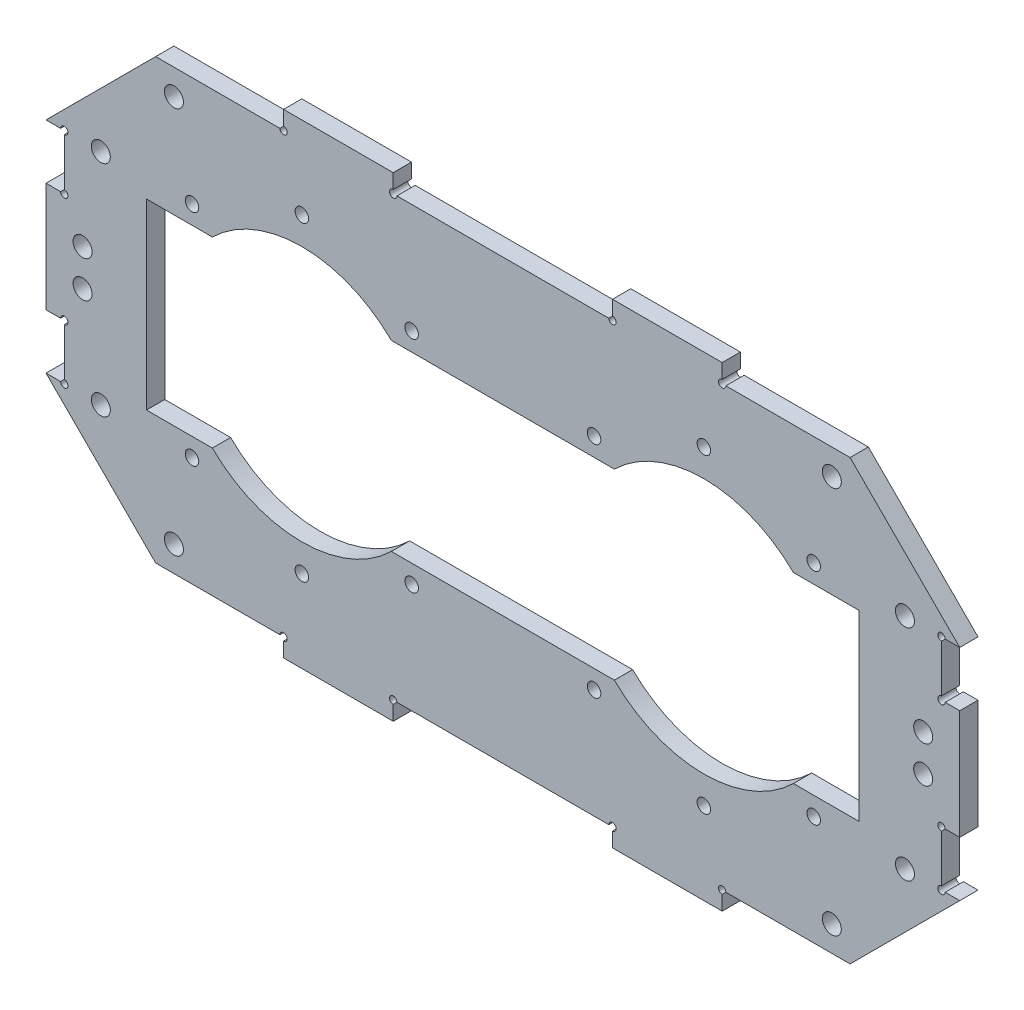
SolidWorks part; units mm, degrees
ref_plane "前视基准面" through (0, 0, 0) normal (0, 0, 1) x (1, 0, 0)
ref_plane "上视基准面" through (0, 0, 0) normal (0, 1, 0) x (1, 0, 0)
ref_plane "右视基准面" through (0, 0, 0) normal (1, 0, 0) x (0, 0, -1)
other "Configuration Table"
sketch "草图1" plane through (0, 0, 0) normal (0, 0, 1) x (1, 0, 0)
  line L36 (95.3994, 59.7004) -> (125.3994, 29.7004)
  line L37 (125.3994, -30.2996) -> (125.3994, 29.7004)
  line L38 (95.3994, -60.2996) -> (125.3994, -30.2996)
  line L39 (-94.6006, -60.2996) -> (95.3994, -60.2996)
  line L40 (95.3994, 59.7004) -> (-94.6006, 59.7004)
  line L41 (-94.6006, -60.2996) -> (-124.6006, -30.2996)
  line L42 (-124.6006, 29.7004) -> (-124.6006, -30.2996)
  line L43 (-94.6006, 59.7004) -> (-124.6006, 29.7004)
extrude "凸台-拉伸1" add sketch "草图1" along normal blind 5
sketch "草图2" plane through (0, 0, 5) normal (0, 0, 1) x (1, 0, 0)
  line L0 (0.3994, 59.7004) -> (0.3994, -60.2996) construction
  line L1 (-124.6006, 29.7004) -> (-119.6006, 29.7004)
  line L2 (-124.6006, 29.7004) -> (-124.6006, 14.7004)
  line L3 (-124.6006, 14.7004) -> (-119.6006, 14.7004)
  line L4 (-119.6006, 29.7004) -> (-119.6006, 14.7004)
  line L5 (-124.6006, -30.2996) -> (-119.6006, -30.2996)
  line L6 (-124.6006, -30.2996) -> (-124.6006, -15.2996)
  line L7 (-124.6006, -15.2996) -> (-119.6006, -15.2996)
  line L8 (95.3994, 59.7004) -> (-94.6006, 59.7004)
  line L9 (-94.6006, 59.7004) -> (-124.6006, 29.7004)
  line L10 (-124.6006, 29.7004) -> (-124.6006, -30.2996)
  line L11 (-124.6006, -30.2996) -> (-94.6006, -60.2996)
  line L12 (-94.6006, -60.2996) -> (95.3994, -60.2996)
  line L13 (95.3994, -60.2996) -> (125.3994, -30.2996)
  line L14 (125.3994, -30.2996) -> (125.3994, 29.7004)
  line L15 (125.3994, 29.7004) -> (95.3994, 59.7004)
  line L16 (95.3994, 59.7004) -> (-94.6006, 59.7004)
  line L17 (-94.6006, 59.7004) -> (-124.6006, 29.7004)
  line L18 (-124.6006, 29.7004) -> (-124.6006, -30.2996)
  line L19 (-124.6006, -30.2996) -> (-94.6006, -60.2996)
  line L20 (-94.6006, -60.2996) -> (95.3994, -60.2996)
  line L21 (95.3994, -60.2996) -> (125.3994, -30.2996)
  line L22 (125.3994, -30.2996) -> (125.3994, 29.7004)
  line L23 (125.3994, 29.7004) -> (95.3994, 59.7004)
  line L24 (-119.6006, -30.2996) -> (-119.6006, -15.2996)
  line L25 (125.3994, -30.2996) -> (120.3994, -30.2996)
  line L26 (120.3994, -30.2996) -> (120.3994, -15.2996)
  line L27 (125.3994, -15.2996) -> (120.3994, -15.2996)
  line L28 (125.3994, -30.2996) -> (125.3994, -15.2996)
  line L29 (125.3994, 29.7004) -> (125.3994, 14.7004)
  line L30 (125.3994, 14.7004) -> (120.3994, 14.7004)
  line L31 (125.3994, 29.7004) -> (120.3994, 29.7004)
  line L32 (120.3994, 29.7004) -> (120.3994, 14.7004)
  line M20 (-124.6006, 29.7004) -> (-124.6006, -30.2996)
  line M24 (125.3994, -30.2996) -> (125.3994, 29.7004)
  dimension "D2" = 5
  dimension "D3" = 5
  dimension "D4" = 15
  dimension "D5" = 15
  dimension "D1" = 0
extrude "切除-拉伸1" cut sketch "草图2" against normal blind 5 contours L4 L1 L3 M20 | L5 L24 L7 M20 | L27 L26 L25 M24 | L31 L32 L30 M24
sketch "草图3" plane through (0, 0, 5) normal (0, 0, 1) x (1, 0, 0)
  line L0 (-124.6006, 14.7004) -> (-124.6006, -15.2996) construction
  line L1 (-94.6006, -60.2996) -> (95.3994, -60.2996) construction
  line L2 (0.3994, 59.7004) -> (0.3994, -60.2996) construction
  line L3 (95.3994, 59.7004) -> (-94.6006, 59.7004) construction
  line L5 (82.8994, 24.7004) -> (112.8994, 24.7004)
  line L7 (82.8994, -25.2996) -> (112.8994, -25.2996)
  line L8 (112.8994, 24.7004) -> (112.8994, -25.2996)
  line L9 (82.8994, 24.7004) -> (112.8994, -25.2996) construction
  line L10 (82.8994, -25.2996) -> (112.8994, 24.7004) construction
  line L11 (-112.1006, -25.2996) -> (112.8994, -25.2996)
  line L12 (-112.1006, -25.2996) -> (-112.1006, 24.7004)
  line L13 (-112.1006, 24.7004) -> (112.8994, 24.7004)
  line L14 (112.8994, -25.2996) -> (112.8994, 24.7004)
  line L15 (-112.1006, -25.2996) -> (112.8994, 24.7004) construction
  line L16 (-112.1006, 24.7004) -> (112.8994, -25.2996) construction
  line L24 (120.3994, 29.7004) -> (125.3994, 29.7004)
  line L25 (125.3994, 29.7004) -> (95.3994, 59.7004)
  line L26 (95.3994, 59.7004) -> (-94.6006, 59.7004)
  line L27 (-94.6006, 59.7004) -> (-124.6006, 29.7004)
  line L28 (-124.6006, 29.7004) -> (-119.6006, 29.7004)
  line L29 (-119.6006, 29.7004) -> (-119.6006, 14.7004)
  line L30 (-119.6006, 14.7004) -> (-124.6006, 14.7004)
  line L31 (-124.6006, 14.7004) -> (-124.6006, -15.2996)
  line L32 (-124.6006, -15.2996) -> (-119.6006, -15.2996)
  line L33 (-119.6006, -15.2996) -> (-119.6006, -30.2996)
  line L34 (-119.6006, -30.2996) -> (-124.6006, -30.2996)
  line L35 (-124.6006, -30.2996) -> (-94.6006, -60.2996)
  line L36 (-94.6006, -60.2996) -> (95.3994, -60.2996)
  line L37 (95.3994, -60.2996) -> (125.3994, -30.2996)
  line L38 (125.3994, -30.2996) -> (120.3994, -30.2996)
  line L39 (120.3994, -30.2996) -> (120.3994, -15.2996)
  line L40 (120.3994, -15.2996) -> (125.3994, -15.2996)
  line L41 (125.3994, -15.2996) -> (125.3994, 14.7004)
  line L42 (125.3994, 14.7004) -> (120.3994, 14.7004)
  line L43 (120.3994, 14.7004) -> (120.3994, 29.7004)
  line L44 (120.3994, 29.7004) -> (125.3994, 29.7004)
  line L45 (125.3994, 29.7004) -> (95.3994, 59.7004)
  line L46 (95.3994, 59.7004) -> (-94.6006, 59.7004)
  line L47 (-94.6006, 59.7004) -> (-124.6006, 29.7004)
  line L48 (-124.6006, 29.7004) -> (-119.6006, 29.7004)
  line L49 (-119.6006, 29.7004) -> (-119.6006, 14.7004)
  line L50 (-119.6006, 14.7004) -> (-124.6006, 14.7004)
  line L51 (-124.6006, 14.7004) -> (-124.6006, -15.2996)
  line L52 (-124.6006, -15.2996) -> (-119.6006, -15.2996)
  line L53 (-119.6006, -15.2996) -> (-119.6006, -30.2996)
  line L54 (-119.6006, -30.2996) -> (-124.6006, -30.2996)
  line L55 (-124.6006, -30.2996) -> (-94.6006, -60.2996)
  line L56 (-94.6006, -60.2996) -> (95.3994, -60.2996)
  line L57 (95.3994, -60.2996) -> (125.3994, -30.2996)
  line L58 (125.3994, -30.2996) -> (120.3994, -30.2996)
  line L59 (120.3994, -30.2996) -> (120.3994, -15.2996)
  line L60 (120.3994, -15.2996) -> (125.3994, -15.2996)
  line L61 (125.3994, -15.2996) -> (125.3994, 14.7004)
  line L62 (125.3994, 14.7004) -> (120.3994, 14.7004)
  line L63 (120.3994, 14.7004) -> (120.3994, 29.7004)
  circle A0 centre (-54.6006, -0.2996) radius 42.5 construction
  circle A1 centre (55.3994, -0.2996) radius 42.5 construction
  circle A2 centre (-54.6006, 42.2004) radius 1.85
  circle A3 centre (-24.5485, 29.7525) radius 1.85
  circle A4 centre (-12.1006, -0.2996) radius 1.85
  circle A5 centre (-24.5485, -30.3516) radius 1.85
  circle A6 centre (-54.6006, -42.7996) radius 1.85
  circle A7 centre (-84.6526, -30.3516) radius 1.85
  circle A8 centre (-97.1006, -0.2996) radius 1.85
  circle A9 centre (-84.6526, 29.7525) radius 1.85
  circle A10 centre (55.3994, 42.2004) radius 1.85
  circle A11 centre (85.4515, 29.7525) radius 1.85
  circle A12 centre (97.8994, -0.2996) radius 1.85
  circle A13 centre (85.4515, -30.3516) radius 1.85
  circle A14 centre (55.3994, -42.7996) radius 1.85
  circle A15 centre (25.3474, -30.3516) radius 1.85
  circle A16 centre (12.8994, -0.2996) radius 1.85
  circle A17 centre (25.3474, 29.7525) radius 1.85
  circle A18 centre (55.3994, -0.2996) radius 35 construction
  circle A19 centre (-54.6006, -0.2996) radius 35 construction
  point P50 (-54.6006, -0.2996)
  point P68 (55.3994, -0.2996)
  point P72 (0.3994, -0.2996)
  dimension "D1" = 85
  dimension "D3" = 60
  dimension "D5" = 3.7
  dimension "D7" = 3.7
  dimension "D9" = 70
  dimension "D10" = 70
  dimension "D2" = 70
  dimension "D11" = 50
  dimension "D12" = 30
  dimension "D13" = 225
  dimension "D14" = 112.5
  dimension "D4" = 0
  dimension "D6" = 8
  dimension "D8" = 8
extrude "切除-拉伸3" cut sketch "草图3" against normal blind 5 contours L13 L12 L11 L7 L8 L5 A16 A12 A8 A4 | A7 | A6 | A5 | A4 | A3 | A15 | A14 | A13 | A11 | A10 | A17 | A16 | A12 | A2 | A9
sketch "草图4" plane through (0, 0, 5) normal (0, 0, 1) x (1, 0, 0)
  line L0 (125.3994, -30.2996) -> (125.3994, 29.7004) construction
  line L1 (-94.6006, 59.7004) -> (-124.6006, 29.7004) construction
  line L2 (95.3994, 59.7004) -> (-94.6006, 59.7004) construction
  line L3 (125.3994, 29.7004) -> (95.3994, 59.7004) construction
  line L4 (-124.6006, -30.2996) -> (-94.6006, -60.2996) construction
  line L5 (-94.6006, -60.2996) -> (95.3994, -60.2996) construction
  line L6 (95.3994, -60.2996) -> (125.3994, -30.2996) construction
  line L7 (-124.6006, 29.7004) -> (-124.6006, -30.2996) construction
  line L8 (125.3994, 29.7004) -> (125.3994, 14.7004) construction
  line L9 (125.3994, 14.7004) -> (120.3994, 14.7004) construction
  line L10 (120.3994, 29.7004) -> (120.3994, 14.7004) construction
  line L11 (125.3994, 29.7004) -> (120.3994, 29.7004) construction
  line L12 (125.3994, -30.2996) -> (120.3994, -30.2996) construction
  line L13 (120.3994, -30.2996) -> (120.3994, -15.2996) construction
  line L14 (125.3994, -15.2996) -> (120.3994, -15.2996) construction
  line L15 (125.3994, -30.2996) -> (125.3994, -15.2996) construction
  line L16 (-124.6006, -30.2996) -> (-119.6006, -30.2996) construction
  line L17 (-119.6006, -30.2996) -> (-119.6006, -15.2996) construction
  line L18 (-124.6006, -15.2996) -> (-119.6006, -15.2996) construction
  line L19 (-124.6006, -30.2996) -> (-124.6006, -15.2996) construction
  line L20 (120.3994, 29.7004) -> (125.3994, 29.7004)
  line L21 (125.3994, 29.7004) -> (95.3994, 59.7004)
  line L22 (95.3994, 59.7004) -> (-94.6006, 59.7004)
  line L23 (-94.6006, 59.7004) -> (-124.6006, 29.7004)
  line L24 (-124.6006, 29.7004) -> (-119.6006, 29.7004)
  line L25 (-119.6006, 29.7004) -> (-119.6006, 14.7004)
  line L26 (-119.6006, 14.7004) -> (-124.6006, 14.7004)
  line L27 (-124.6006, 14.7004) -> (-124.6006, -15.2996)
  line L28 (-124.6006, -15.2996) -> (-119.6006, -15.2996)
  line L29 (-119.6006, -15.2996) -> (-119.6006, -30.2996)
  line L30 (-119.6006, -30.2996) -> (-124.6006, -30.2996)
  line L31 (-124.6006, -30.2996) -> (-94.6006, -60.2996)
  line L32 (-94.6006, -60.2996) -> (95.3994, -60.2996)
  line L33 (95.3994, -60.2996) -> (125.3994, -30.2996)
  line L34 (125.3994, -30.2996) -> (120.3994, -30.2996)
  line L35 (120.3994, -30.2996) -> (120.3994, -15.2996)
  line L36 (120.3994, -15.2996) -> (125.3994, -15.2996)
  line L37 (125.3994, -15.2996) -> (125.3994, 14.7004)
  line L38 (125.3994, 14.7004) -> (120.3994, 14.7004)
  line L39 (120.3994, 14.7004) -> (120.3994, 29.7004)
  line L40 (120.3994, 29.7004) -> (125.3994, 29.7004)
  line L41 (125.3994, 29.7004) -> (95.3994, 59.7004)
  line L42 (95.3994, 59.7004) -> (-94.6006, 59.7004)
  line L43 (-94.6006, 59.7004) -> (-124.6006, 29.7004)
  line L44 (-124.6006, 29.7004) -> (-119.6006, 29.7004)
  line L45 (-119.6006, 29.7004) -> (-119.6006, 14.7004)
  line L46 (-119.6006, 14.7004) -> (-124.6006, 14.7004)
  line L47 (-124.6006, 14.7004) -> (-124.6006, -15.2996)
  line L48 (-124.6006, -15.2996) -> (-119.6006, -15.2996)
  line L49 (-119.6006, -15.2996) -> (-119.6006, -30.2996)
  line L50 (-119.6006, -30.2996) -> (-124.6006, -30.2996)
  line L51 (-124.6006, -30.2996) -> (-94.6006, -60.2996)
  line L52 (-94.6006, -60.2996) -> (95.3994, -60.2996)
  line L53 (95.3994, -60.2996) -> (125.3994, -30.2996)
  line L54 (125.3994, -30.2996) -> (120.3994, -30.2996)
  line L55 (120.3994, -30.2996) -> (120.3994, -15.2996)
  line L56 (120.3994, -15.2996) -> (125.3994, -15.2996)
  line L57 (125.3994, -15.2996) -> (125.3994, 14.7004)
  line L58 (125.3994, 14.7004) -> (120.3994, 14.7004)
  line L59 (120.3994, 14.7004) -> (120.3994, 29.7004)
  line L60 (-124.6006, 29.7004) -> (-119.6006, 29.7004) construction
  line L61 (-119.6006, 29.7004) -> (-119.6006, 14.7004) construction
  line L62 (-124.6006, 14.7004) -> (-119.6006, 14.7004) construction
  line L63 (-124.6006, 29.7004) -> (-124.6006, 14.7004) construction
  line L64 (125.3994, -30.2996) -> (125.3994, 29.7004)
  line L65 (-94.6006, 59.7004) -> (-124.6006, 29.7004)
  line L66 (95.3994, 59.7004) -> (-94.6006, 59.7004)
  line L67 (125.3994, 29.7004) -> (95.3994, 59.7004)
  line L68 (-124.6006, -30.2996) -> (-94.6006, -60.2996)
  line L69 (-94.6006, -60.2996) -> (95.3994, -60.2996)
  line L70 (95.3994, -60.2996) -> (125.3994, -30.2996)
  line L71 (-124.6006, 29.7004) -> (-124.6006, -30.2996)
  line L72 (125.3994, 29.7004) -> (125.3994, 14.7004)
  line L73 (125.3994, 14.7004) -> (120.3994, 14.7004)
  line L74 (120.3994, 29.7004) -> (120.3994, 14.7004)
  line L75 (125.3994, 29.7004) -> (120.3994, 29.7004)
  line L76 (125.3994, -30.2996) -> (120.3994, -30.2996)
  line L77 (120.3994, -30.2996) -> (120.3994, -15.2996)
  line L78 (125.3994, -15.2996) -> (120.3994, -15.2996)
  line L79 (125.3994, -30.2996) -> (125.3994, -15.2996)
  line L80 (-124.6006, -30.2996) -> (-119.6006, -30.2996)
  line L81 (-119.6006, -30.2996) -> (-119.6006, -15.2996)
  line L82 (-124.6006, -15.2996) -> (-119.6006, -15.2996)
  line L83 (-124.6006, -30.2996) -> (-124.6006, -15.2996)
  line L84 (-124.6006, 29.7004) -> (-119.6006, 29.7004)
  line L85 (-119.6006, 29.7004) -> (-119.6006, 14.7004)
  line L86 (-124.6006, 14.7004) -> (-119.6006, 14.7004)
  line L87 (-124.6006, 29.7004) -> (-124.6006, 14.7004)
  line L88 (82.8994, -25.2996) -> (112.8994, -25.2996) construction
  line L89 (112.8994, 24.7004) -> (112.8994, -25.2996) construction
  line L90 (-112.1006, -25.2996) -> (112.8994, -25.2996) construction
  line L91 (-112.1006, -25.2996) -> (-112.1006, 24.7004) construction
  line L92 (-112.1006, 24.7004) -> (112.8994, 24.7004) construction
  line L93 (112.8994, -25.2996) -> (112.8994, 24.7004) construction
  line L94 (82.8994, 24.7004) -> (112.8994, 24.7004) construction
  line L95 (82.8994, -25.2996) -> (112.8994, -25.2996)
  line L96 (112.8994, 24.7004) -> (112.8994, -25.2996)
  line L97 (-112.1006, -25.2996) -> (112.8994, -25.2996)
  line L98 (-112.1006, -25.2996) -> (-112.1006, 24.7004)
  line L99 (-112.1006, 24.7004) -> (112.8994, 24.7004)
  line L100 (112.8994, -25.2996) -> (112.8994, 24.7004)
  line L101 (82.8994, 24.7004) -> (112.8994, 24.7004)
  line L102 (0.3994, 59.7004) -> (0.3994, -60.2996) construction
  line L108 (120.3994, 14.7004) -> (120.3994, 29.7004)
  line L109 (120.3994, 29.7004) -> (125.3994, 29.7004)
  line L110 (125.3994, 29.7004) -> (95.3994, 59.7004)
  line L111 (95.3994, 59.7004) -> (-94.6006, 59.7004)
  line L112 (-94.6006, 59.7004) -> (-124.6006, 29.7004)
  line L113 (-124.6006, 29.7004) -> (-119.6006, 29.7004)
  line L114 (-119.6006, 29.7004) -> (-119.6006, 14.7004)
  line L115 (-119.6006, 14.7004) -> (-124.6006, 14.7004)
  line L116 (-124.6006, 14.7004) -> (-124.6006, -15.2996)
  line L117 (-124.6006, -15.2996) -> (-119.6006, -15.2996)
  line L118 (-119.6006, -15.2996) -> (-119.6006, -30.2996)
  line L119 (-119.6006, -30.2996) -> (-124.6006, -30.2996)
  line L120 (-124.6006, -30.2996) -> (-94.6006, -60.2996)
  line L121 (-94.6006, -60.2996) -> (95.3994, -60.2996)
  line L122 (95.3994, -60.2996) -> (125.3994, -30.2996)
  line L123 (125.3994, -30.2996) -> (120.3994, -30.2996)
  line L124 (120.3994, -30.2996) -> (120.3994, -15.2996)
  line L125 (120.3994, -15.2996) -> (125.3994, -15.2996)
  line L126 (125.3994, -15.2996) -> (125.3994, 14.7004)
  line L127 (125.3994, 14.7004) -> (120.3994, 14.7004)
  line L128 (120.3994, 14.7004) -> (120.3994, 29.7004)
  line L129 (120.3994, 29.7004) -> (125.3994, 29.7004)
  line L130 (125.3994, 29.7004) -> (95.3994, 59.7004)
  line L131 (95.3994, 59.7004) -> (-94.6006, 59.7004)
  line L132 (-94.6006, 59.7004) -> (-124.6006, 29.7004)
  line L133 (-124.6006, 29.7004) -> (-119.6006, 29.7004)
  line L134 (-119.6006, 29.7004) -> (-119.6006, 14.7004)
  line L135 (-119.6006, 14.7004) -> (-124.6006, 14.7004)
  line L136 (-124.6006, 14.7004) -> (-124.6006, -15.2996)
  line L137 (-124.6006, -15.2996) -> (-119.6006, -15.2996)
  line L138 (-119.6006, -15.2996) -> (-119.6006, -30.2996)
  line L139 (-119.6006, -30.2996) -> (-124.6006, -30.2996)
  line L140 (-124.6006, -30.2996) -> (-94.6006, -60.2996)
  line L141 (-94.6006, -60.2996) -> (95.3994, -60.2996)
  line L142 (95.3994, -60.2996) -> (125.3994, -30.2996)
  line L143 (125.3994, -30.2996) -> (120.3994, -30.2996)
  line L144 (120.3994, -30.2996) -> (120.3994, -15.2996)
  line L145 (120.3994, -15.2996) -> (125.3994, -15.2996)
  line L146 (125.3994, -15.2996) -> (125.3994, 14.7004)
  line L147 (125.3994, 14.7004) -> (120.3994, 14.7004)
  circle A0 centre (-54.6006, -0.2996) radius 35
  circle A1 centre (-12.1006, -0.2996) radius 1.85
  circle A2 centre (-12.1006, -0.2996) radius 1.85
  circle A3 centre (-24.5485, 29.7525) radius 1.85
  circle A4 centre (-24.5485, 29.7525) radius 1.85
  circle A5 centre (-54.6006, 42.2004) radius 1.85
  circle A6 centre (-54.6006, 42.2004) radius 1.85
  circle A7 centre (-97.1006, -0.2996) radius 1.85
  circle A8 centre (-97.1006, -0.2996) radius 1.85
  circle A9 centre (-84.6526, -30.3516) radius 1.85
  circle A10 centre (-84.6526, -30.3516) radius 1.85
  circle A11 centre (-54.6006, -42.7996) radius 1.85
  circle A12 centre (-54.6006, -42.7996) radius 1.85
  circle A13 centre (-24.5485, -30.3516) radius 1.85
  circle A14 centre (-24.5485, -30.3516) radius 1.85
  circle A15 centre (25.3474, -30.3516) radius 1.85
  circle A16 centre (25.3474, -30.3516) radius 1.85
  circle A17 centre (55.3994, -42.7996) radius 1.85
  circle A18 centre (55.3994, -42.7996) radius 1.85
  circle A19 centre (85.4515, -30.3516) radius 1.85
  circle A20 centre (85.4515, -30.3516) radius 1.85
  circle A21 centre (97.8994, -0.2996) radius 1.85
  circle A22 centre (97.8994, -0.2996) radius 1.85
  circle A23 centre (85.4515, 29.7525) radius 1.85
  circle A24 centre (85.4515, 29.7525) radius 1.85
  circle A25 centre (55.3994, 42.2004) radius 1.85
  circle A26 centre (55.3994, 42.2004) radius 1.85
  circle A27 centre (-84.6526, 29.7525) radius 1.85
  circle A28 centre (-84.6526, 29.7525) radius 1.85
  circle A29 centre (25.3474, 29.7525) radius 1.85
  circle A30 centre (25.3474, 29.7525) radius 1.85
  circle A31 centre (12.8994, -0.2996) radius 1.85
  circle A32 centre (12.8994, -0.2996) radius 1.85
  circle A33 centre (55.3994, -0.2996) radius 35
  dimension "D20" = 60
  dimension "D21" = 70
  dimension "D19" = 70
  dimension "D1" = 0
  dimension "D2" = 0
  dimension "D3" = 0
  dimension "D4" = 0
  dimension "D5" = 0
  dimension "D6" = 0
  dimension "D7" = 0
  dimension "D8" = 0
  dimension "D9" = 0
  dimension "D10" = 0
  dimension "D11" = 0
  dimension "D12" = 0
  dimension "D13" = 0
  dimension "D14" = 0
  dimension "D15" = 0
  dimension "D16" = 0
  dimension "D17" = 0
  dimension "D18" = 0
extrude "切除-拉伸4" cut sketch "草图4" against normal blind 5 contours L99 A0 | L97 A0 | A33 L97 | A33 L99
sketch "草图5" plane through (0, 0, 5) normal (0, 0, 1) x (1, 0, 0)
  line L0 (0.3994, 59.7004) -> (0.3994, -60.2996)
  line L20 (120.3994, 29.7004) -> (125.3994, 29.7004)
  line L21 (125.3994, 29.7004) -> (95.3994, 59.7004)
  line L22 (95.3994, 59.7004) -> (-94.6006, 59.7004)
  line L23 (-94.6006, 59.7004) -> (-124.6006, 29.7004)
  line L24 (-124.6006, 29.7004) -> (-119.6006, 29.7004)
  line L25 (-119.6006, 29.7004) -> (-119.6006, 14.7004)
  line L26 (-119.6006, 14.7004) -> (-124.6006, 14.7004)
  line L27 (-124.6006, 14.7004) -> (-124.6006, -15.2996)
  line L28 (-124.6006, -15.2996) -> (-119.6006, -15.2996)
  line L29 (-119.6006, -15.2996) -> (-119.6006, -30.2996)
  line L30 (-119.6006, -30.2996) -> (-124.6006, -30.2996)
  line L31 (-124.6006, -30.2996) -> (-94.6006, -60.2996)
  line L32 (-94.6006, -60.2996) -> (95.3994, -60.2996)
  line L33 (95.3994, -60.2996) -> (125.3994, -30.2996)
  line L34 (125.3994, -30.2996) -> (120.3994, -30.2996)
  line L35 (120.3994, -30.2996) -> (120.3994, -15.2996)
  line L36 (120.3994, -15.2996) -> (125.3994, -15.2996)
  line L37 (125.3994, -15.2996) -> (125.3994, 14.7004)
  line L38 (125.3994, 14.7004) -> (120.3994, 14.7004)
  line L39 (120.3994, 14.7004) -> (120.3994, 29.7004)
  line L40 (120.3994, 29.7004) -> (125.3994, 29.7004)
  line L41 (125.3994, 29.7004) -> (95.3994, 59.7004)
  line L42 (95.3994, 59.7004) -> (-94.6006, 59.7004)
  line L43 (-94.6006, 59.7004) -> (-124.6006, 29.7004)
  line L44 (-124.6006, 29.7004) -> (-119.6006, 29.7004)
  line L45 (-119.6006, 29.7004) -> (-119.6006, 14.7004)
  line L46 (-119.6006, 14.7004) -> (-124.6006, 14.7004)
  line L47 (-124.6006, 14.7004) -> (-124.6006, -15.2996)
  line L48 (-124.6006, -15.2996) -> (-119.6006, -15.2996)
  line L49 (-119.6006, -15.2996) -> (-119.6006, -30.2996)
  line L50 (-119.6006, -30.2996) -> (-124.6006, -30.2996)
  line L51 (-124.6006, -30.2996) -> (-94.6006, -60.2996)
  line L52 (-94.6006, -60.2996) -> (95.3994, -60.2996)
  line L53 (95.3994, -60.2996) -> (125.3994, -30.2996)
  line L54 (125.3994, -30.2996) -> (120.3994, -30.2996)
  line L55 (120.3994, -30.2996) -> (120.3994, -15.2996)
  line L56 (120.3994, -15.2996) -> (125.3994, -15.2996)
  line L57 (125.3994, -15.2996) -> (125.3994, 14.7004)
  line L58 (125.3994, 14.7004) -> (120.3994, 14.7004)
  line L59 (120.3994, 14.7004) -> (120.3994, 29.7004)
  circle A0 centre (-119.6006, 29.7004) radius 1
  circle A1 centre (-119.6006, 14.7004) radius 1
  circle A2 centre (-119.6006, -15.2996) radius 1
  circle A3 centre (-119.6006, -30.2996) radius 1
  circle A4 centre (120.3994, -30.2996) radius 1
  circle A5 centre (120.3994, -15.2996) radius 1
  circle A6 centre (120.3994, 14.7004) radius 1
  circle A7 centre (120.3994, 29.7004) radius 1
  line M37 (120.3994, 29.7004) -> (125.3994, 29.7004)
  line M42 (-119.6006, 29.7004) -> (-119.6006, 14.7004)
  line M43 (-119.6006, 14.7004) -> (-124.6006, 14.7004)
  line M46 (-119.6006, -15.2996) -> (-119.6006, -30.2996)
  line M47 (-119.6006, -30.2996) -> (-124.6006, -30.2996)
  line M52 (120.3994, -30.2996) -> (120.3994, -15.2996)
  line M53 (120.3994, -15.2996) -> (125.3994, -15.2996)
  line M56 (120.3994, 14.7004) -> (120.3994, 29.7004)
  dimension "D2" = 2
  dimension "D3" = 2
  dimension "D4" = 2
  dimension "D5" = 2
  dimension "D1" = 0
extrude "切除-拉伸5" cut sketch "草图5" against normal blind 5 contours A0 L44 M42 | A1 M43 M42 | A2 L48 M46 | A3 M47 M46 | A7 M56 M37 | A6 L58 M56 | A5 M52 M53 | A4 L54 M52
sketch "草图6" plane through (-112.1006, 0, 0) normal (1, 0, 0) x (0, 0, -1)
  line L4 (-5, 24.7004) -> (-5, -25.2996)
  line L5 (-5, -25.2996) -> (0, -25.2996)
  line L6 (0, -25.2996) -> (0, 24.7004)
  line L7 (0, 24.7004) -> (-5, 24.7004)
  line L8 (-5, 24.7004) -> (-5, -25.2996)
  line L9 (-5, -25.2996) -> (0, -25.2996)
  line L10 (0, -25.2996) -> (0, 24.7004)
  line L11 (0, 24.7004) -> (-5, 24.7004)
  dimension "D1" = 0
extrude "凸台-拉伸2" add sketch "草图6" along normal blind 15
sketch "草图7" plane through (112.8994, 0, 0) normal (-1, 0, 0) x (0, 0, 1)
  line L4 (5, -25.2996) -> (5, 24.7004)
  line L5 (5, 24.7004) -> (0, 24.7004)
  line L6 (0, 24.7004) -> (0, -25.2996)
  line L7 (0, -25.2996) -> (5, -25.2996)
  line L8 (5, -25.2996) -> (5, 24.7004)
  line L9 (5, 24.7004) -> (0, 24.7004)
  line L10 (0, 24.7004) -> (0, -25.2996)
  line L11 (0, -25.2996) -> (5, -25.2996)
  dimension "D1" = 0
extrude "凸台-拉伸3" add sketch "草图7" along normal blind 15
sketch "草图8" plane through (0, 0, 5) normal (0, 0, 1) x (1, 0, 0)
  line L0 (0.3994, 59.7004) -> (0.3994, -60.2996)
  line L1 (-59.6006, 59.7004) -> (-29.6006, 59.7004)
  line L2 (-59.6006, 59.7004) -> (-59.6006, 64.7004)
  line L3 (-59.6006, 64.7004) -> (-29.6006, 64.7004)
  line L4 (-29.6006, 59.7004) -> (-29.6006, 64.7004)
  line L5 (-124.6006, -0.2996) -> (125.3994, -0.2996)
  line L6 (-59.6006, -65.2996) -> (-29.6006, -65.2996)
  line L7 (-29.6006, -60.2996) -> (-29.6006, -65.2996)
  line L8 (-59.6006, -60.2996) -> (-29.6006, -60.2996)
  line L9 (-59.6006, -60.2996) -> (-59.6006, -65.2996)
  line L10 (60.3994, 64.7004) -> (30.3994, 64.7004)
  line L11 (30.3994, 59.7004) -> (30.3994, 64.7004)
  line L12 (60.3994, 59.7004) -> (30.3994, 59.7004)
  line L13 (60.3994, 59.7004) -> (60.3994, 64.7004)
  line L14 (60.3994, -60.2996) -> (60.3994, -65.2996)
  line L15 (60.3994, -60.2996) -> (30.3994, -60.2996)
  line L16 (30.3994, -60.2996) -> (30.3994, -65.2996)
  line L17 (60.3994, -65.2996) -> (30.3994, -65.2996)
  line L20 (120.3994, 15.7004) -> (120.3994, 28.7004)
  line L21 (121.3994, 29.7004) -> (125.3994, 29.7004)
  line L22 (125.3994, 29.7004) -> (95.3994, 59.7004)
  line L23 (95.3994, 59.7004) -> (-94.6006, 59.7004)
  line L24 (-94.6006, 59.7004) -> (-124.6006, 29.7004)
  line L25 (-124.6006, 29.7004) -> (-120.6006, 29.7004)
  line L26 (-119.6006, 28.7004) -> (-119.6006, 15.7004)
  line L27 (-120.6006, 14.7004) -> (-124.6006, 14.7004)
  line L28 (-124.6006, 14.7004) -> (-124.6006, -15.2996)
  line L29 (-124.6006, -15.2996) -> (-120.6006, -15.2996)
  line L30 (-119.6006, -16.2996) -> (-119.6006, -29.2996)
  line L31 (-120.6006, -30.2996) -> (-124.6006, -30.2996)
  line L32 (-124.6006, -30.2996) -> (-94.6006, -60.2996)
  line L33 (-94.6006, -60.2996) -> (95.3994, -60.2996)
  line L34 (95.3994, -60.2996) -> (125.3994, -30.2996)
  line L35 (125.3994, -30.2996) -> (121.3994, -30.2996)
  line L36 (120.3994, -29.2996) -> (120.3994, -16.2996)
  line L37 (121.3994, -15.2996) -> (125.3994, -15.2996)
  line L38 (125.3994, -15.2996) -> (125.3994, 14.7004)
  line L39 (125.3994, 14.7004) -> (121.3994, 14.7004)
  line L40 (120.3994, 15.7004) -> (120.3994, 28.7004)
  line L41 (121.3994, 29.7004) -> (125.3994, 29.7004)
  line L42 (125.3994, 29.7004) -> (95.3994, 59.7004)
  line L43 (95.3994, 59.7004) -> (-94.6006, 59.7004)
  line L44 (-94.6006, 59.7004) -> (-124.6006, 29.7004)
  line L45 (-124.6006, 29.7004) -> (-120.6006, 29.7004)
  line L46 (-119.6006, 28.7004) -> (-119.6006, 15.7004)
  line L47 (-120.6006, 14.7004) -> (-124.6006, 14.7004)
  line L48 (-124.6006, 14.7004) -> (-124.6006, -15.2996)
  line L49 (-124.6006, -15.2996) -> (-120.6006, -15.2996)
  line L50 (-119.6006, -16.2996) -> (-119.6006, -29.2996)
  line L51 (-120.6006, -30.2996) -> (-124.6006, -30.2996)
  line L52 (-124.6006, -30.2996) -> (-94.6006, -60.2996)
  line L53 (-94.6006, -60.2996) -> (95.3994, -60.2996)
  line L54 (95.3994, -60.2996) -> (125.3994, -30.2996)
  line L55 (125.3994, -30.2996) -> (121.3994, -30.2996)
  line L56 (120.3994, -29.2996) -> (120.3994, -16.2996)
  line L57 (121.3994, -15.2996) -> (125.3994, -15.2996)
  line L58 (125.3994, -15.2996) -> (125.3994, 14.7004)
  line L59 (125.3994, 14.7004) -> (121.3994, 14.7004)
  circle A0 centre (-59.6006, 59.7004) radius 1
  circle A1 centre (-29.6006, 59.7004) radius 1
  circle A2 centre (-29.6006, -60.2996) radius 1
  circle A3 centre (-59.6006, -60.2996) radius 1
  circle A4 centre (30.3994, -60.2996) radius 1
  circle A5 centre (60.3994, -60.2996) radius 1
  circle A6 centre (30.3994, 59.7004) radius 1
  circle A7 centre (60.3994, 59.7004) radius 1
  arc A8 (121.3994, 29.7004) -> (120.3994, 28.7004) centre (120.3994, 29.7004) ccw
  arc A9 (-119.6006, 28.7004) -> (-120.6006, 29.7004) centre (-119.6006, 29.7004) ccw
  arc A10 (-120.6006, 14.7004) -> (-119.6006, 15.7004) centre (-119.6006, 14.7004) ccw
  arc A11 (-119.6006, -16.2996) -> (-120.6006, -15.2996) centre (-119.6006, -15.2996) ccw
  arc A12 (-120.6006, -30.2996) -> (-119.6006, -29.2996) centre (-119.6006, -30.2996) ccw
  arc A13 (120.3994, -29.2996) -> (121.3994, -30.2996) centre (120.3994, -30.2996) ccw
  arc A14 (121.3994, -15.2996) -> (120.3994, -16.2996) centre (120.3994, -15.2996) ccw
  arc A15 (120.3994, 15.7004) -> (121.3994, 14.7004) centre (120.3994, 14.7004) ccw
  arc A16 (121.3994, 29.7004) -> (120.3994, 28.7004) centre (120.3994, 29.7004) ccw
  arc A17 (-119.6006, 28.7004) -> (-120.6006, 29.7004) centre (-119.6006, 29.7004) ccw
  arc A18 (-120.6006, 14.7004) -> (-119.6006, 15.7004) centre (-119.6006, 14.7004) ccw
  arc A19 (-119.6006, -16.2996) -> (-120.6006, -15.2996) centre (-119.6006, -15.2996) ccw
  arc A20 (-120.6006, -30.2996) -> (-119.6006, -29.2996) centre (-119.6006, -30.2996) ccw
  arc A21 (120.3994, -29.2996) -> (121.3994, -30.2996) centre (120.3994, -30.2996) ccw
  arc A22 (121.3994, -15.2996) -> (120.3994, -16.2996) centre (120.3994, -15.2996) ccw
  arc A23 (120.3994, 15.7004) -> (121.3994, 14.7004) centre (120.3994, 14.7004) ccw
  point P31 (-29.6006, 62.2004)
  dimension "D5" = 2
  dimension "D6" = 2
  dimension "D2" = 30
  dimension "D3" = 30
  dimension "D4" = 5
  dimension "D1" = 0
extrude "凸台-拉伸4" add sketch "草图8" against normal blind 5 contours A1 L4 L3 L2 A0 L43 | L53 A3 L9 L6 L7 A2 | L15 L16 L17 L14 | L10 L11 L12 L13
sketch "草图9" plane through (0, 0, 5) normal (0, 0, 1) x (1, 0, 0)
  line L0 (-124.6006, -0.2996) -> (125.3994, -0.2996) construction
  line L1 (0.3994, 59.7004) -> (0.3994, -60.2996) construction
  line L2 (-124.6006, -0.2996) -> (125.3994, -0.2996)
  line L3 (0.3994, 59.7004) -> (0.3994, -60.2996)
  line L4 (-59.6006, 59.7004) -> (-29.6006, 59.7004)
  line L5 (-59.6006, 64.7004) -> (-59.6006, 59.7004)
  line L6 (-29.6006, 64.7004) -> (-59.6006, 64.7004)
  line L7 (-29.6006, 59.7004) -> (-29.6006, 64.7004)
  line L8 (-59.6006, 59.7004) -> (-29.6006, 59.7004)
  line L9 (-59.6006, 64.7004) -> (-59.6006, 59.7004)
  line L10 (-29.6006, 64.7004) -> (-59.6006, 64.7004)
  line L11 (-29.6006, 59.7004) -> (-29.6006, 64.7004)
  line L12 (60.3994, 64.7004) -> (30.3994, 64.7004)
  line L13 (30.3994, 64.7004) -> (30.3994, 59.7004)
  line L14 (30.3994, 59.7004) -> (60.3994, 59.7004)
  line L15 (60.3994, 59.7004) -> (60.3994, 64.7004)
  line L16 (60.3994, 64.7004) -> (30.3994, 64.7004)
  line L17 (30.3994, 64.7004) -> (30.3994, 59.7004)
  line L18 (30.3994, 59.7004) -> (60.3994, 59.7004)
  line L19 (60.3994, 59.7004) -> (60.3994, 64.7004)
  line L20 (-59.6006, -65.2996) -> (-29.6006, -65.2996)
  line L21 (-29.6006, -65.2996) -> (-29.6006, -60.2996)
  line L22 (-29.6006, -60.2996) -> (-59.6006, -60.2996)
  line L23 (-59.6006, -60.2996) -> (-59.6006, -65.2996)
  line L24 (-59.6006, -65.2996) -> (-29.6006, -65.2996)
  line L25 (-29.6006, -65.2996) -> (-29.6006, -60.2996)
  line L26 (-29.6006, -60.2996) -> (-59.6006, -60.2996)
  line L27 (-59.6006, -60.2996) -> (-59.6006, -65.2996)
  line L28 (60.3994, -65.2996) -> (60.3994, -60.2996)
  line L29 (60.3994, -60.2996) -> (30.3994, -60.2996)
  line L30 (30.3994, -60.2996) -> (30.3994, -65.2996)
  line L31 (30.3994, -65.2996) -> (60.3994, -65.2996)
  line L32 (60.3994, -65.2996) -> (60.3994, -60.2996)
  line L33 (60.3994, -60.2996) -> (30.3994, -60.2996)
  line L34 (30.3994, -60.2996) -> (30.3994, -65.2996)
  line L35 (30.3994, -65.2996) -> (60.3994, -65.2996)
  line L44 (120.3994, -29.2996) -> (120.3994, -16.2996)
  line L45 (121.3994, -15.2996) -> (125.3994, -15.2996)
  line L46 (125.3994, -15.2996) -> (125.3994, 14.7004)
  line L47 (125.3994, 14.7004) -> (121.3994, 14.7004)
  line L48 (120.3994, 15.7004) -> (120.3994, 28.7004)
  line L49 (121.3994, 29.7004) -> (125.3994, 29.7004)
  line L50 (125.3994, 29.7004) -> (95.3994, 59.7004)
  line L51 (95.3994, 59.7004) -> (-94.6006, 59.7004)
  line L52 (-94.6006, 59.7004) -> (-124.6006, 29.7004)
  line L53 (-124.6006, 29.7004) -> (-120.6006, 29.7004)
  line L54 (-119.6006, 28.7004) -> (-119.6006, 15.7004)
  line L55 (-120.6006, 14.7004) -> (-124.6006, 14.7004)
  line L56 (-124.6006, 14.7004) -> (-124.6006, -15.2996)
  line L57 (-124.6006, -15.2996) -> (-120.6006, -15.2996)
  line L58 (-119.6006, -16.2996) -> (-119.6006, -29.2996)
  line L59 (-120.6006, -30.2996) -> (-124.6006, -30.2996)
  line L60 (-124.6006, -30.2996) -> (-94.6006, -60.2996)
  line L61 (-94.6006, -60.2996) -> (95.3994, -60.2996)
  line L62 (95.3994, -60.2996) -> (125.3994, -30.2996)
  line L63 (125.3994, -30.2996) -> (121.3994, -30.2996)
  line L64 (120.3994, -29.2996) -> (120.3994, -16.2996)
  line L65 (121.3994, -15.2996) -> (125.3994, -15.2996)
  line L66 (125.3994, -15.2996) -> (125.3994, 14.7004)
  line L67 (125.3994, 14.7004) -> (121.3994, 14.7004)
  line L68 (120.3994, 15.7004) -> (120.3994, 28.7004)
  line L69 (121.3994, 29.7004) -> (125.3994, 29.7004)
  line L70 (125.3994, 29.7004) -> (95.3994, 59.7004)
  line L71 (95.3994, 59.7004) -> (-94.6006, 59.7004)
  line L72 (-94.6006, 59.7004) -> (-124.6006, 29.7004)
  line L73 (-124.6006, 29.7004) -> (-120.6006, 29.7004)
  line L74 (-119.6006, 28.7004) -> (-119.6006, 15.7004)
  line L75 (-120.6006, 14.7004) -> (-124.6006, 14.7004)
  line L76 (-124.6006, 14.7004) -> (-124.6006, -15.2996)
  line L77 (-124.6006, -15.2996) -> (-120.6006, -15.2996)
  line L78 (-119.6006, -16.2996) -> (-119.6006, -29.2996)
  line L79 (-120.6006, -30.2996) -> (-124.6006, -30.2996)
  line L80 (-124.6006, -30.2996) -> (-94.6006, -60.2996)
  line L81 (-94.6006, -60.2996) -> (95.3994, -60.2996)
  line L82 (95.3994, -60.2996) -> (125.3994, -30.2996)
  line L83 (125.3994, -30.2996) -> (121.3994, -30.2996)
  circle A1 centre (30.3994, 59.7004) radius 1
  circle A2 centre (30.3994, 59.7004) radius 1
  circle A3 centre (60.3994, -60.2996) radius 1
  circle A4 centre (60.3994, -60.2996) radius 1
  circle A5 centre (30.3994, -60.2996) radius 1
  circle A6 centre (30.3994, -60.2996) radius 1
  circle A7 centre (-59.6006, -60.2996) radius 1
  circle A8 centre (-59.6006, -60.2996) radius 1
  circle A9 centre (-29.6006, -60.2996) radius 1
  circle A10 centre (-29.6006, -60.2996) radius 1
  circle A11 centre (-29.6006, 59.7004) radius 1
  circle A12 centre (-29.6006, 59.7004) radius 1
  circle A13 centre (-59.6006, 59.7004) radius 1
  circle A14 centre (-59.6006, 59.7004) radius 1
  circle A15 centre (60.3994, 59.7004) radius 1
  circle A16 centre (60.3994, 59.7004) radius 1
  arc A22 (121.3994, -15.2996) -> (120.3994, -16.2996) centre (120.3994, -15.2996) ccw
  arc A23 (120.3994, 15.7004) -> (121.3994, 14.7004) centre (120.3994, 14.7004) ccw
  arc A24 (121.3994, 29.7004) -> (120.3994, 28.7004) centre (120.3994, 29.7004) ccw
  arc A25 (-119.6006, 28.7004) -> (-120.6006, 29.7004) centre (-119.6006, 29.7004) ccw
  arc A26 (-120.6006, 14.7004) -> (-119.6006, 15.7004) centre (-119.6006, 14.7004) ccw
  arc A27 (-119.6006, -16.2996) -> (-120.6006, -15.2996) centre (-119.6006, -15.2996) ccw
  arc A28 (-120.6006, -30.2996) -> (-119.6006, -29.2996) centre (-119.6006, -30.2996) ccw
  arc A29 (120.3994, -29.2996) -> (121.3994, -30.2996) centre (120.3994, -30.2996) ccw
  arc A30 (121.3994, -15.2996) -> (120.3994, -16.2996) centre (120.3994, -15.2996) ccw
  arc A31 (120.3994, 15.7004) -> (121.3994, 14.7004) centre (120.3994, 14.7004) ccw
  arc A32 (121.3994, 29.7004) -> (120.3994, 28.7004) centre (120.3994, 29.7004) ccw
  arc A33 (-119.6006, 28.7004) -> (-120.6006, 29.7004) centre (-119.6006, 29.7004) ccw
  arc A34 (-120.6006, 14.7004) -> (-119.6006, 15.7004) centre (-119.6006, 14.7004) ccw
  arc A35 (-119.6006, -16.2996) -> (-120.6006, -15.2996) centre (-119.6006, -15.2996) ccw
  arc A36 (-120.6006, -30.2996) -> (-119.6006, -29.2996) centre (-119.6006, -30.2996) ccw
  arc A37 (120.3994, -29.2996) -> (121.3994, -30.2996) centre (120.3994, -30.2996) ccw
  dimension "D1" = 0
  dimension "D2" = 0
  dimension "D3" = 0
  dimension "D4" = 0
  dimension "D5" = 0
  dimension "D6" = 0
  dimension "D7" = 0
  dimension "D8" = 0
  dimension "D9" = 0
  dimension "D10" = 0
  dimension "D11" = 0
  dimension "D12" = 0
  dimension "D13" = 0
extrude "切除-拉伸6" cut sketch "草图9" against normal blind 5 contours L71 A14 L8 | L71 A12 | L71 A2 L18 | L18 A16 L71 | L81 A8 | L81 A10 L26 | L33 A6 L81 | L81 A4 L33
sketch "草图10" plane through (0, 0, 5) normal (0, 0, 1) x (1, 0, 0)
  line L0 (-124.6006, -0.2996) -> (-97.1006, -0.2996)
  line L1 (-97.1006, 24.7004) -> (-97.1006, -25.2996) construction
  line L2 (-64.6006, -60.2996) -> (-64.6006, -36.7734)
  line L3 (0.3994, 59.7004) -> (0.3994, -60.2996)
  line L4 (-124.6006, -0.2996) -> (125.3994, -0.2996)
  line L36 (29.3994, 59.7004) -> (-28.6006, 59.7004)
  line L37 (-29.6006, 60.7004) -> (-29.6006, 64.7004)
  line L38 (-29.6006, 64.7004) -> (-59.6006, 64.7004)
  line L39 (-59.6006, 64.7004) -> (-59.6006, 60.7004)
  line L40 (-60.6006, 59.7004) -> (-94.6006, 59.7004)
  line L41 (-94.6006, 59.7004) -> (-124.6006, 29.7004)
  line L42 (-124.6006, 29.7004) -> (-120.6006, 29.7004)
  line L43 (-119.6006, 28.7004) -> (-119.6006, 15.7004)
  line L44 (-120.6006, 14.7004) -> (-124.6006, 14.7004)
  line L45 (-124.6006, 14.7004) -> (-124.6006, -15.2996)
  line L46 (-124.6006, -15.2996) -> (-120.6006, -15.2996)
  line L47 (-119.6006, -16.2996) -> (-119.6006, -29.2996)
  line L48 (-120.6006, -30.2996) -> (-124.6006, -30.2996)
  line L49 (-124.6006, -30.2996) -> (-94.6006, -60.2996)
  line L50 (-94.6006, -60.2996) -> (-60.6006, -60.2996)
  line L51 (-59.6006, -61.2996) -> (-59.6006, -65.2996)
  line L52 (-59.6006, -65.2996) -> (-29.6006, -65.2996)
  line L53 (-29.6006, -65.2996) -> (-29.6006, -61.2996)
  line L54 (-28.6006, -60.2996) -> (29.3994, -60.2996)
  line L55 (30.3994, -61.2996) -> (30.3994, -65.2996)
  line L56 (30.3994, -65.2996) -> (60.3994, -65.2996)
  line L57 (60.3994, -65.2996) -> (60.3994, -61.2996)
  line L58 (61.3994, -60.2996) -> (95.3994, -60.2996)
  line L59 (95.3994, -60.2996) -> (125.3994, -30.2996)
  line L60 (125.3994, -30.2996) -> (121.3994, -30.2996)
  line L61 (120.3994, -29.2996) -> (120.3994, -16.2996)
  line L62 (121.3994, -15.2996) -> (125.3994, -15.2996)
  line L63 (125.3994, -15.2996) -> (125.3994, 14.7004)
  line L64 (125.3994, 14.7004) -> (121.3994, 14.7004)
  line L65 (120.3994, 15.7004) -> (120.3994, 28.7004)
  line L66 (121.3994, 29.7004) -> (125.3994, 29.7004)
  line L67 (125.3994, 29.7004) -> (95.3994, 59.7004)
  line L68 (95.3994, 59.7004) -> (61.3994, 59.7004)
  line L69 (60.3994, 60.7004) -> (60.3994, 64.7004)
  line L70 (60.3994, 64.7004) -> (30.3994, 64.7004)
  line L71 (30.3994, 64.7004) -> (30.3994, 60.7004)
  line L72 (29.3994, 59.7004) -> (-28.6006, 59.7004)
  line L73 (-29.6006, 60.7004) -> (-29.6006, 64.7004)
  line L74 (-29.6006, 64.7004) -> (-59.6006, 64.7004)
  line L75 (-59.6006, 64.7004) -> (-59.6006, 60.7004)
  line L76 (-60.6006, 59.7004) -> (-94.6006, 59.7004)
  line L77 (-94.6006, 59.7004) -> (-124.6006, 29.7004)
  line L78 (-124.6006, 29.7004) -> (-120.6006, 29.7004)
  line L79 (-119.6006, 28.7004) -> (-119.6006, 15.7004)
  line L80 (-120.6006, 14.7004) -> (-124.6006, 14.7004)
  line L81 (-124.6006, 14.7004) -> (-124.6006, -15.2996)
  line L82 (-124.6006, -15.2996) -> (-120.6006, -15.2996)
  line L83 (-119.6006, -16.2996) -> (-119.6006, -29.2996)
  line L84 (-120.6006, -30.2996) -> (-124.6006, -30.2996)
  line L85 (-124.6006, -30.2996) -> (-94.6006, -60.2996)
  line L86 (-94.6006, -60.2996) -> (-60.6006, -60.2996)
  line L87 (-59.6006, -61.2996) -> (-59.6006, -65.2996)
  line L88 (-59.6006, -65.2996) -> (-29.6006, -65.2996)
  line L89 (-29.6006, -65.2996) -> (-29.6006, -61.2996)
  line L90 (-28.6006, -60.2996) -> (29.3994, -60.2996)
  line L91 (30.3994, -61.2996) -> (30.3994, -65.2996)
  line L92 (30.3994, -65.2996) -> (60.3994, -65.2996)
  line L93 (60.3994, -65.2996) -> (60.3994, -61.2996)
  line L94 (61.3994, -60.2996) -> (95.3994, -60.2996)
  line L95 (95.3994, -60.2996) -> (125.3994, -30.2996)
  line L96 (125.3994, -30.2996) -> (121.3994, -30.2996)
  line L97 (120.3994, -29.2996) -> (120.3994, -16.2996)
  line L98 (121.3994, -15.2996) -> (125.3994, -15.2996)
  line L99 (125.3994, -15.2996) -> (125.3994, 14.7004)
  line L100 (125.3994, 14.7004) -> (121.3994, 14.7004)
  line L101 (120.3994, 15.7004) -> (120.3994, 28.7004)
  line L102 (121.3994, 29.7004) -> (125.3994, 29.7004)
  line L103 (125.3994, 29.7004) -> (95.3994, 59.7004)
  line L104 (95.3994, 59.7004) -> (61.3994, 59.7004)
  line L105 (60.3994, 60.7004) -> (60.3994, 64.7004)
  line L106 (60.3994, 64.7004) -> (30.3994, 64.7004)
  line L107 (30.3994, 64.7004) -> (30.3994, 60.7004)
  circle A0 centre (-114.6006, -5.2996) radius 2.6
  circle A1 centre (-109.6006, -30.2996) radius 2.6
  circle A2 centre (-89.6006, -53.2996) radius 2.6
  circle A3 centre (90.3994, -53.2996) radius 2.6
  circle A4 centre (110.3994, -30.2996) radius 2.6
  circle A5 centre (115.3994, -5.2996) radius 2.6
  circle A6 centre (115.3994, 4.7004) radius 2.6
  circle A7 centre (110.3994, 29.7004) radius 2.6
  circle A8 centre (90.3994, 52.7004) radius 2.6
  circle A9 centre (-89.6006, 52.7004) radius 2.6
  circle A10 centre (-109.6006, 29.7004) radius 2.6
  circle A11 centre (-114.6006, 4.7004) radius 2.6
  arc A16 (-29.6006, 60.7004) -> (-28.6006, 59.7004) centre (-29.6006, 59.7004) ccw
  arc A17 (-60.6006, 59.7004) -> (-59.6006, 60.7004) centre (-59.6006, 59.7004) ccw
  arc A18 (-119.6006, 28.7004) -> (-120.6006, 29.7004) centre (-119.6006, 29.7004) ccw
  arc A19 (-120.6006, 14.7004) -> (-119.6006, 15.7004) centre (-119.6006, 14.7004) ccw
  arc A20 (-119.6006, -16.2996) -> (-120.6006, -15.2996) centre (-119.6006, -15.2996) ccw
  arc A21 (-120.6006, -30.2996) -> (-119.6006, -29.2996) centre (-119.6006, -30.2996) ccw
  arc A22 (-59.6006, -61.2996) -> (-60.6006, -60.2996) centre (-59.6006, -60.2996) ccw
  arc A23 (-28.6006, -60.2996) -> (-29.6006, -61.2996) centre (-29.6006, -60.2996) ccw
  arc A24 (30.3994, -61.2996) -> (29.3994, -60.2996) centre (30.3994, -60.2996) ccw
  arc A25 (61.3994, -60.2996) -> (60.3994, -61.2996) centre (60.3994, -60.2996) ccw
  arc A26 (120.3994, -29.2996) -> (121.3994, -30.2996) centre (120.3994, -30.2996) ccw
  arc A27 (121.3994, -15.2996) -> (120.3994, -16.2996) centre (120.3994, -15.2996) ccw
  arc A28 (120.3994, 15.7004) -> (121.3994, 14.7004) centre (120.3994, 14.7004) ccw
  arc A29 (121.3994, 29.7004) -> (120.3994, 28.7004) centre (120.3994, 29.7004) ccw
  arc A30 (60.3994, 60.7004) -> (61.3994, 59.7004) centre (60.3994, 59.7004) ccw
  arc A31 (29.3994, 59.7004) -> (30.3994, 60.7004) centre (30.3994, 59.7004) ccw
  arc A32 (-29.6006, 60.7004) -> (-28.6006, 59.7004) centre (-29.6006, 59.7004) ccw
  arc A33 (-60.6006, 59.7004) -> (-59.6006, 60.7004) centre (-59.6006, 59.7004) ccw
  arc A34 (-119.6006, 28.7004) -> (-120.6006, 29.7004) centre (-119.6006, 29.7004) ccw
  arc A35 (-120.6006, 14.7004) -> (-119.6006, 15.7004) centre (-119.6006, 14.7004) ccw
  arc A36 (-119.6006, -16.2996) -> (-120.6006, -15.2996) centre (-119.6006, -15.2996) ccw
  arc A37 (-120.6006, -30.2996) -> (-119.6006, -29.2996) centre (-119.6006, -30.2996) ccw
  arc A38 (-59.6006, -61.2996) -> (-60.6006, -60.2996) centre (-59.6006, -60.2996) ccw
  arc A39 (-28.6006, -60.2996) -> (-29.6006, -61.2996) centre (-29.6006, -60.2996) ccw
  arc A40 (30.3994, -61.2996) -> (29.3994, -60.2996) centre (30.3994, -60.2996) ccw
  arc A41 (61.3994, -60.2996) -> (60.3994, -61.2996) centre (60.3994, -60.2996) ccw
  arc A42 (120.3994, -29.2996) -> (121.3994, -30.2996) centre (120.3994, -30.2996) ccw
  arc A43 (121.3994, -15.2996) -> (120.3994, -16.2996) centre (120.3994, -15.2996) ccw
  arc A44 (120.3994, 15.7004) -> (121.3994, 14.7004) centre (120.3994, 14.7004) ccw
  arc A45 (121.3994, 29.7004) -> (120.3994, 28.7004) centre (120.3994, 29.7004) ccw
  arc A46 (60.3994, 60.7004) -> (61.3994, 59.7004) centre (60.3994, 59.7004) ccw
  arc A47 (29.3994, 59.7004) -> (30.3994, 60.7004) centre (30.3994, 59.7004) ccw
  dimension "D2" = 5.2
  dimension "D3" = 5.2
  dimension "D4" = 10
  dimension "D5" = 15
  dimension "D10" = 5.2
  dimension "D11" = 7
  dimension "D6" = 30
  dimension "D7" = 5
  dimension "D8" = 30
  dimension "D9" = 25
  dimension "D1" = 0
extrude "切除-拉伸7" cut sketch "草图10" against normal through all contours A0 | A1 | A2 | A5 | A4 | A3 | A11 | A10 | A9 | A8 | A7 | A6
